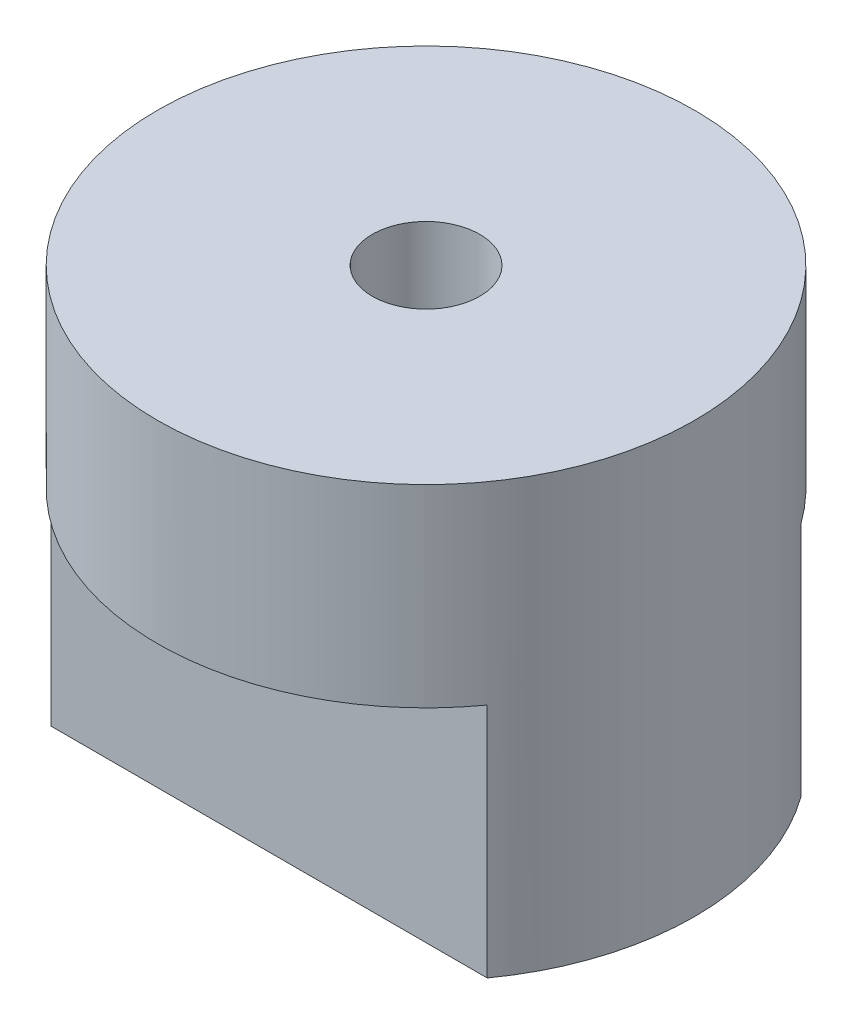
SolidWorks part; units mm, degrees
ref_plane "Front Plane" through (0, 0, 0) normal (0, 0, 1) x (1, 0, 0)
ref_plane "Top Plane" through (0, 0, 0) normal (0, 1, 0) x (1, 0, 0)
ref_plane "Right Plane" through (0, 0, 0) normal (1, 0, 0) x (0, 0, -1)
sketch "Sketch1" plane through (0, 0, 0) normal (0, 1, 0) x (1, 0, 0)
  circle A0 centre (0, 0) radius 15.875
  dimension "D1" = 31.75
extrude "Boss-Extrude1" add sketch "Sketch1" along normal blind 25.4
sketch "Sketch2" plane through (0, 0, 0) normal (1, 0, 0) x (0, 0, -1)
  line L0 (0, 0) -> (0, 50000) construction
  line L1 (-15.875, 0) -> (15.875, 0) construction
  line L2 (15.875, 0) -> (9.271, 0)
  line L3 (-15.875, 0) -> (-9.271, 0)
  line L4 (-15.875, 0) -> (-15.875, 13.97)
  line L5 (-15.875, 13.97) -> (-9.271, 13.97)
  line L6 (-9.271, 0) -> (-9.271, 13.97)
  line L7 (9.271, 0) -> (9.271, 13.97)
  line L8 (15.875, 0) -> (15.875, 13.97)
  line L9 (15.875, 13.97) -> (9.271, 13.97)
  point P4 (0, 0)
  dimension "D1" = 18.542
  dimension "D2" = 13.97
extrude "Cut-Extrude1" cut sketch "Sketch2" against normal through all and the other way through all
sketch "Sketch3" plane through (0, 25.4, 0) normal (0, 1, 0) x (1, 0, 0)
  circle A0 centre (0, 0) radius 3.175
  dimension "D1" = 6.35
extrude "Cut-Extrude2" cut sketch "Sketch3" against normal blind 12.7
